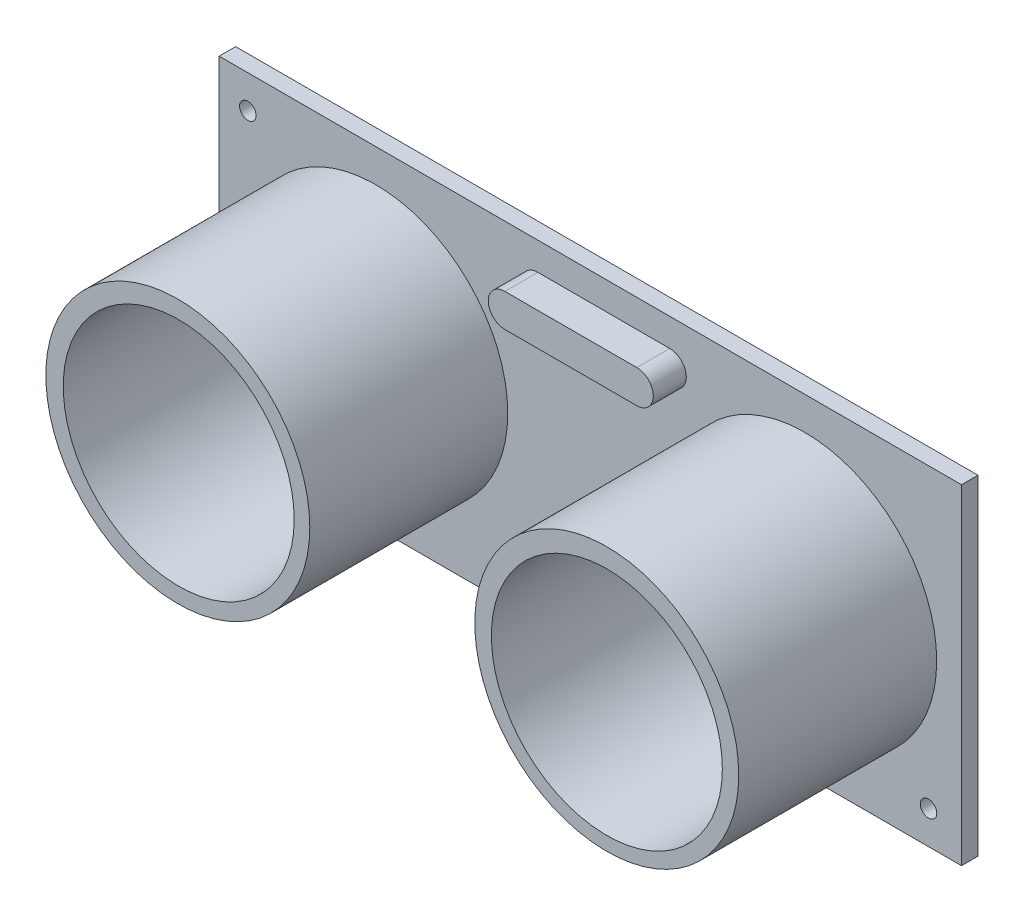
SolidWorks part; units mm, degrees
ref_plane "Front Plane" through (0, 0, 0) normal (0, 0, 1) x (1, 0, 0)
ref_plane "Top Plane" through (0, 0, 0) normal (0, 1, 0) x (1, 0, 0)
ref_plane "Right Plane" through (0, 0, 0) normal (1, 0, 0) x (0, 0, -1)
sketch "Sketch1" plane through (0, 0, 0) normal (0, 0, 1) x (1, 0, 0)
  line L1 (23.0503, -9.606) -> (-21.9497, -9.606)
  line L2 (23.0503, -9.606) -> (23.0503, 10.394)
  line L3 (23.0503, 10.394) -> (-21.9497, 10.394)
  line L4 (-21.9497, -9.606) -> (-21.9497, 10.394)
  line L5 (23.0503, -9.606) -> (-21.9497, 10.394) construction
  line L6 (23.0503, 10.394) -> (-21.9497, -9.606) construction
  point P0 (0.5503, 0.394)
  dimension "D1" = 45
  dimension "D2" = 20
extrude "Boss-Extrude1" add sketch "Sketch1" along normal blind 1
sketch "Sketch2" plane through (0, 0, 1) normal (0, 0, 1) x (1, 0, 0)
  line L0 (-21.9497, -9.606) -> (23.0503, -9.606) construction
  circle A0 centre (-12.4529, 0.394) radius 8
  circle A1 centre (13.5471, 0.394) radius 8
  circle A2 centre (-12.3981, 0.3393) radius 7
  circle A3 centre (13.5534, 0.2298) radius 7
  dimension "D1" = 16
  dimension "D3" = 16
  dimension "D5" = 14
  dimension "D6" = 14
  dimension "D2" = 10
  dimension "D4" = 26
extrude "Boss-Extrude2" add sketch "Sketch2" along normal blind 12
sketch "Sketch4" plane through (0, 0, 1) normal (0, 0, 1) x (1, 0, 0)
  line L0 (-2.631, 7.7046) -> (5.369, 7.7046) construction
  line L1 (-2.631, 8.7046) -> (5.369, 8.7046)
  line L2 (-2.631, 6.7046) -> (5.369, 6.7046)
  line L3 (-12.8361, 0.175) -> (14.8153, 0.175)
  arc A0 (-2.631, 8.7046) -> (-2.631, 6.7046) centre (-2.631, 7.7046) ccw
  arc A1 (5.369, 6.7046) -> (5.369, 8.7046) centre (5.369, 7.7046) ccw
  point P2 (1.369, 7.7046)
  dimension "D2" = 1
  dimension "D1" = 8
extrude "Boss-Extrude3" add sketch "Sketch4" along normal blind 2 contours L1 A1 L2 A0
sketch "Sketch5" plane through (0, 0, 1) normal (0, 0, 1) x (1, 0, 0)
  circle A0 centre (-3.6197, -7.6005) radius 1
  circle A1 centre (-1.1197, -7.6005) radius 1
  circle A2 centre (1.3803, -7.6005) radius 1
  circle A3 centre (3.8803, -7.6005) radius 0.915
  dimension "D1" = 2
  dimension "D2" = 2
  dimension "D3" = 2
  dimension "D4" = 1.8301
  dimension "D5" = 2.5
  dimension "D6" = 2.5
  dimension "D7" = 2.5
extrude "Boss-Extrude4" add sketch "Sketch5" along normal blind 1
sketch "Sketch6" plane through (0, 0, 1) normal (0, 0, 1) x (1, 0, 0)
  line L0 (23.0503, -9.606) -> (23.0503, 10.394) construction
  line L1 (-21.9497, -9.606) -> (23.0503, -9.606) construction
  line L2 (23.0503, 10.394) -> (-21.9497, 10.394) construction
  circle A0 centre (-20.2097, 8.394) radius 0.5
  circle A1 centre (21.0503, -7.606) radius 0.5
  dimension "D1" = 1
  dimension "D2" = 1
  dimension "D3" = 2
  dimension "D4" = 2
  dimension "D5" = 2
extrude "Cut-Extrude1" cut sketch "Sketch6" against normal blind 1
